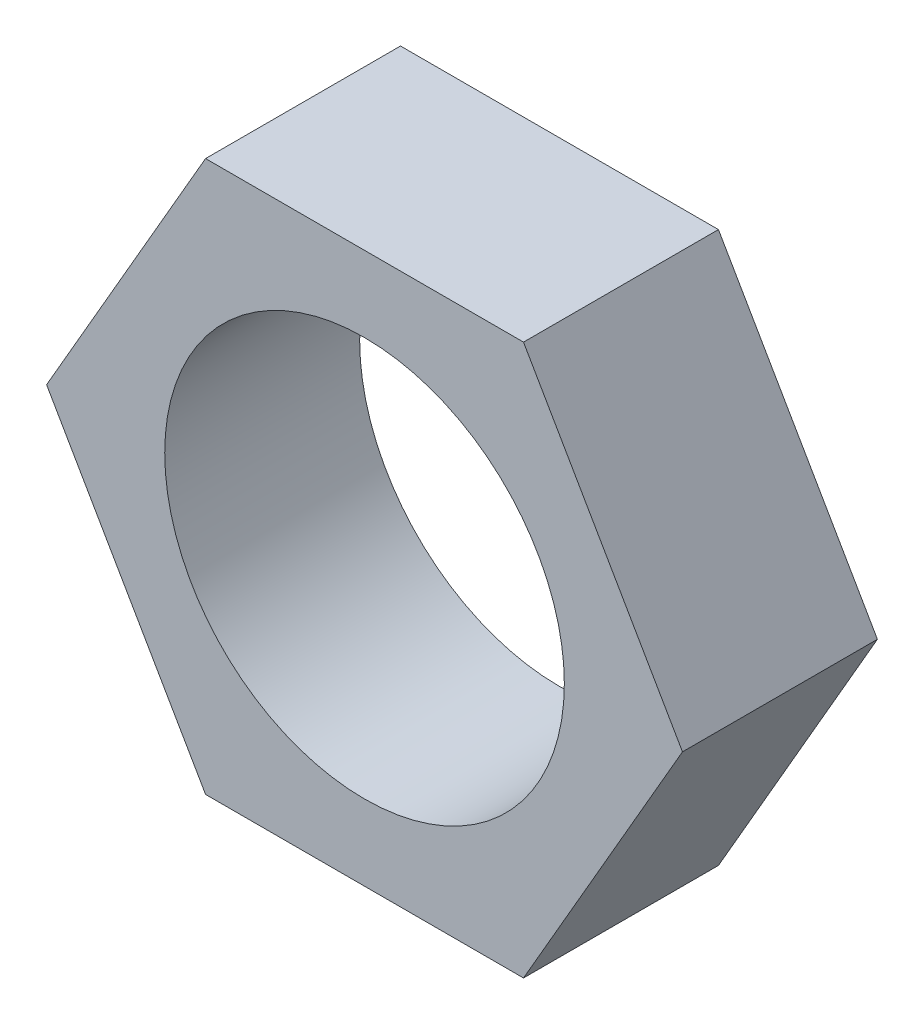
SolidWorks part; units mm, degrees
ref_plane "Front Plane" through (0, 0, 0) normal (0, 0, 1) x (1, 0, 0)
ref_plane "Top Plane" through (0, 0, 0) normal (0, 1, 0) x (1, 0, 0)
ref_plane "Right Plane" through (0, 0, 0) normal (1, 0, 0) x (0, 0, -1)
sketch "Sketch1" plane through (0, 0, 0) normal (0, 0, 1) x (1, 0, 0)
  line L0 (-6.5241, 0) -> (6.5241, 0) construction
  line L1 (3.262, 5.65) -> (-3.262, 5.65)
  line L2 (-3.262, 5.65) -> (-6.5241, 0)
  line L3 (-6.5241, 0) -> (-3.262, -5.65)
  line L4 (-3.262, -5.65) -> (3.262, -5.65)
  line L5 (3.262, -5.65) -> (6.5241, 0)
  line L6 (6.5241, 0) -> (3.262, 5.65)
  line L7 (55, 0) -> (-55, 0) construction
  circle A1 centre (0, 0) radius 5.65 construction
  dimension "D1" = 11.3
extrude "Boss-Extrude1" add sketch "Sketch1" along normal mid plane 4
sketch "Sketch3" plane through (0, 0, 0) normal (0, 0, 1) x (1, 0, 0)
  circle A0 centre (0, 0) radius 4.1
  dimension "D1" = 8.2
extrude "Cut-Extrude1" cut sketch "Sketch3" against normal through all both and the other way through all
